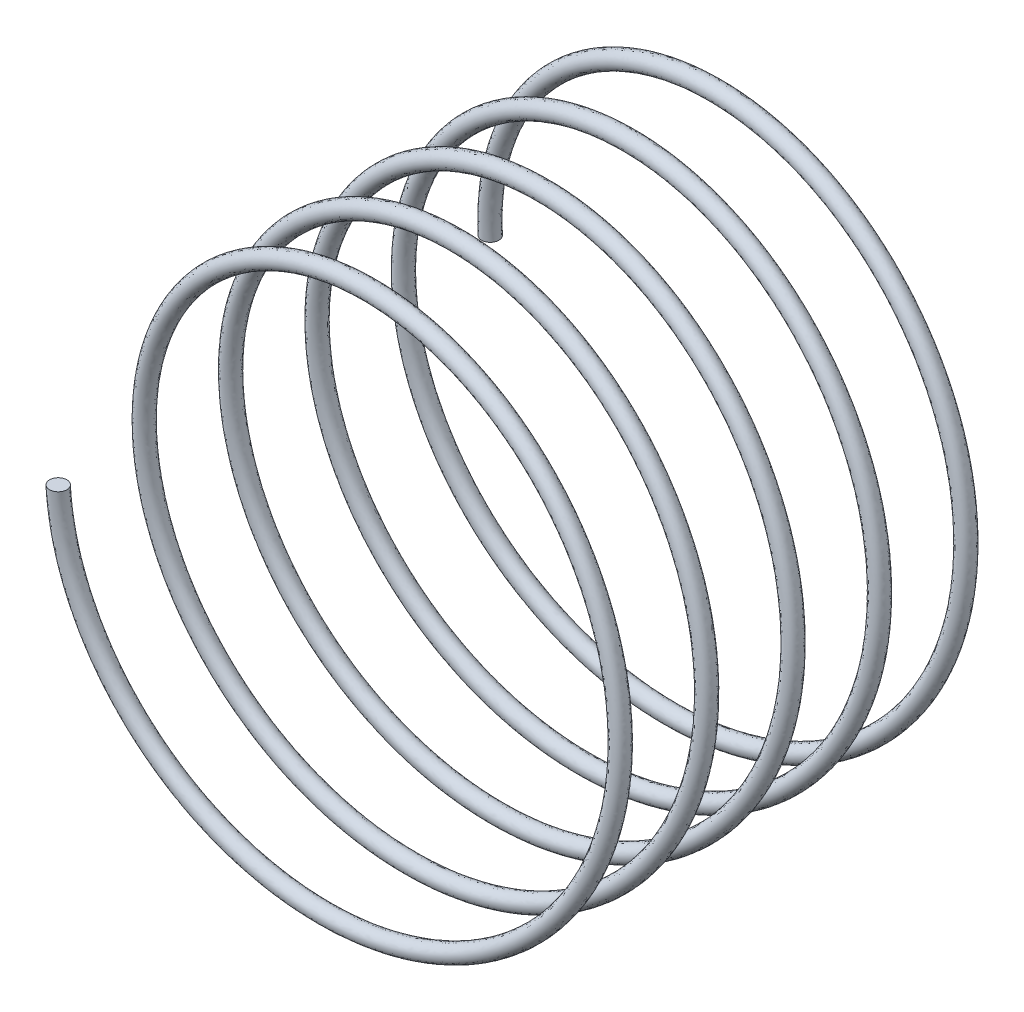
SolidWorks part; units mm, degrees
ref_plane "Plano frontal" through (0, 0, 0) normal (0, 0, 1) x (1, 0, 0)
ref_plane "Plano superior" through (0, 0, 0) normal (0, 1, 0) x (1, 0, 0)
ref_plane "Plano direito" through (0, 0, 0) normal (1, 0, 0) x (0, 0, -1)
sketch "Esboço1" plane through (0, 0, 0) normal (0, 0, 1) x (1, 0, 0)
  circle A0 centre (0, 0) radius 30
  dimension "D1" = 60
curve "Hélice/Espiral2" pitch 10 height 50 turns 5
sketch "Esboço3" plane through (0, 0, 0) normal (0, 1, 0) x (1, 0, 0)
  circle A0 centre (-29.9999, -49.9951) radius 1
  spline S0 degree 3 poles (-30, 0) (-30, -0.1374) (-29.3221, -0.4134) (-26.3397, -0.8264) (-21.5917, -1.2397) (-15.3963, -1.6529) (-8.1689, -2.0661) (-0.3938, -2.4793) (7.4076, -2.8926) (14.7124, -3.3058) (21.0311, -3.719) (25.94, -4.1322) (29.11, -4.5455) (30.3287, -4.9587) (29.5144, -5.3719) (26.7217, -5.7851) (22.1377, -6.1983) (16.0698, -6.6116) (8.9246, -7.0248) (1.1813, -7.438) (-6.6413, -7.8512) (-14.0187, -8.2645) (-20.4563, -8.6777) (-25.5227, -9.0909) (-28.8783, -9.5041) (-30.2981, -9.9174) (-29.6868, -10.3306) (-27.0856, -10.7438) (-22.6688, -11.157) (-16.7324, -11.5702) (-9.6744, -11.9835) (-1.9679, -12.3967) (5.8705, -12.8099) (13.3155, -13.2231) (19.8678, -13.6364) (25.0883, -14.0496) (28.6271, -14.4628) (30.247, -14.876) (29.8393, -15.2893) (27.4313, -15.7025) (23.1846, -16.1157) (17.3838, -16.5289) (10.4176, -16.9421) (2.7532, -17.3554) (-5.0958, -17.7686) (-12.6033, -18.1818) (-19.2658, -18.595) (-24.637, -19.0083) (-28.3567, -19.4215) (-30.1755, -19.8347) (-29.9716, -20.2479) (-27.7586, -20.6612) (-23.6848, -21.0744) (-18.0234, -21.4876) (-11.1539, -21.9008) (-3.5366, -22.314) (4.3177, -22.7273) (11.8826, -23.1405) (18.6509, -23.5537) (24.1691, -23.9669) (28.0671, -24.3802) (30.0837, -24.7934) (30.0837, -25.2066) (28.0671, -25.6198) (24.1691, -26.0331) (18.6509, -26.4463) (11.8826, -26.8595) (4.3177, -27.2727) (-3.5366, -27.686) (-11.1539, -28.0992) (-18.0234, -28.5124) (-23.6848, -28.9256) (-27.7586, -29.3388) (-29.9716, -29.7521) (-30.1755, -30.1653) (-28.3567, -30.5785) (-24.637, -30.9917) (-19.2658, -31.405) (-12.6033, -31.8182) (-5.0958, -32.2314) (2.7532, -32.6446) (10.4176, -33.0579) (17.3838, -33.4711) (23.1846, -33.8843) (27.4313, -34.2975) (29.8393, -34.7107) (30.247, -35.124) (28.6271, -35.5372) (25.0883, -35.9504) (19.8678, -36.3636) (13.3155, -36.7769) (5.8705, -37.1901) (-1.9679, -37.6033) (-9.6744, -38.0165) (-16.7324, -38.4298) (-22.6688, -38.843) (-27.0856, -39.2562) (-29.6868, -39.6694) (-30.2981, -40.0826) (-28.8783, -40.4959) (-25.5227, -40.9091) (-20.4563, -41.3223) (-14.0187, -41.7355) (-6.6413, -42.1488) (1.1813, -42.562) (8.9246, -42.9752) (16.0698, -43.3884) (22.1377, -43.8017) (26.7217, -44.2149) (29.5144, -44.6281) (30.3287, -45.0413) (29.11, -45.4545) (25.94, -45.8678) (21.0311, -46.281) (14.7124, -46.6942) (7.4076, -47.1074) (-0.3938, -47.5207) (-8.1689, -47.9339) (-15.3963, -48.3471) (-21.5917, -48.7603) (-26.3397, -49.1736) (-29.3221, -49.5866) (-30, -49.8626) (-30, -50) knots 0 0 0 0 0.008264 0.016529 0.024793 0.033058 0.041322 0.049587 0.057851 0.066116 0.07438 0.082645 0.090909 0.099174 0.107438 0.115702 0.123967 0.132231 0.140496 0.14876 0.157025 0.165289 0.173554 0.181818 0.190083 0.198347 0.206612 0.214876 0.22314 0.231405 0.239669 0.247934 0.256198 0.264463 0.272727 0.280992 0.289256 0.297521 0.305785 0.31405 0.322314 0.330579 0.338843 0.347107 0.355372 0.363636 0.371901 0.380165 0.38843 0.396694 0.404959 0.413223 0.421488 0.429752 0.438017 0.446281 0.454545 0.46281 0.471074 0.479339 0.487603 0.495868 0.504132 0.512397 0.520661 0.528926 0.53719 0.545455 0.553719 0.561983 0.570248 0.578512 0.586777 0.595041 0.603306 0.61157 0.619835 0.628099 0.636364 0.644628 0.652893 0.661157 0.669421 0.677686 0.68595 0.694215 0.702479 0.710744 0.719008 0.727273 0.735537 0.743802 0.752066 0.760331 0.768595 0.77686 0.785124 0.793388 0.801653 0.809917 0.818182 0.826446 0.834711 0.842975 0.85124 0.859504 0.867769 0.876033 0.884298 0.892562 0.900826 0.909091 0.917355 0.92562 0.933884 0.942149 0.950413 0.958678 0.966942 0.975207 0.983471 0.991736 1 1 1 1 construction
  dimension "D1" = 2
sweep "Varredura1" add profiles "Esboço3" path "Hélice/Espiral2"
